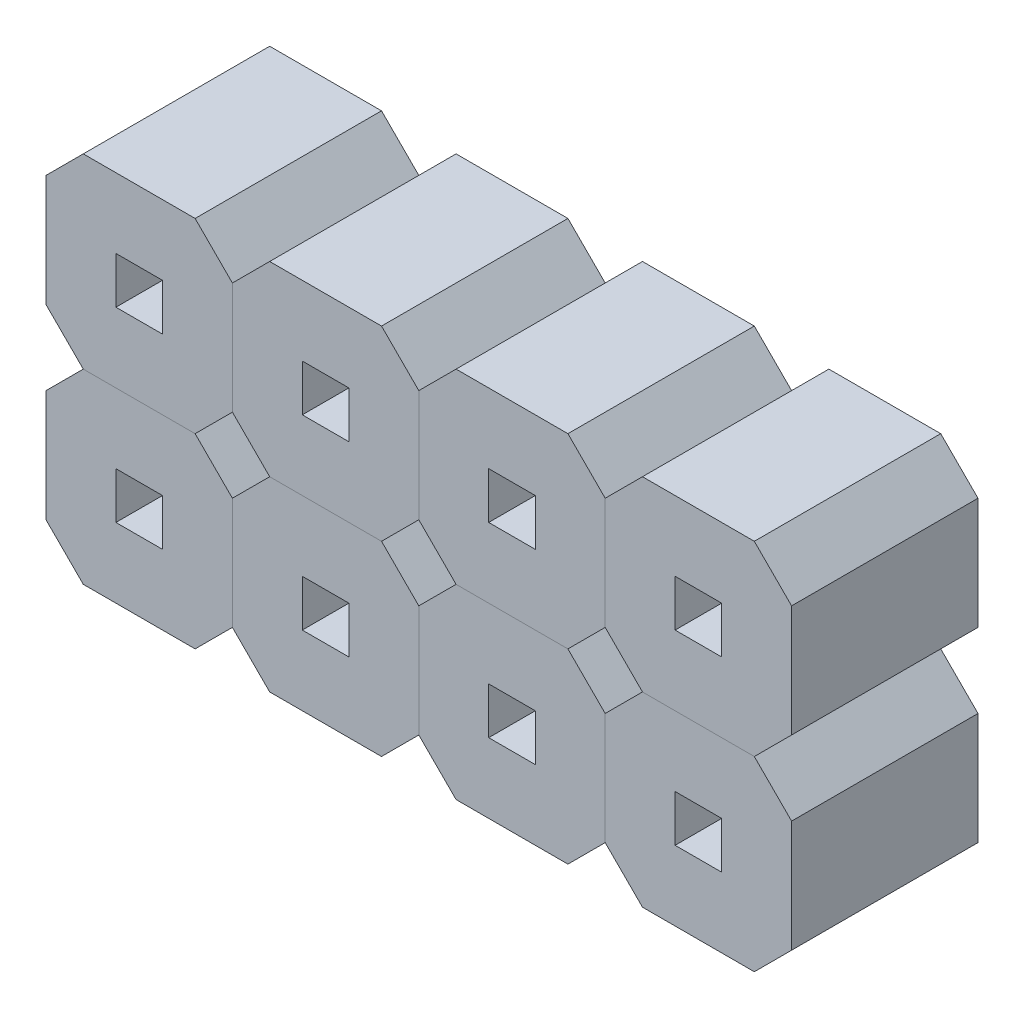
SolidWorks part; units mm, degrees
material "Nylon 6/10"
ref_plane "Front Plane" through (0, 0, 0) normal (0, 0, 1) x (1, 0, 0)
ref_plane "Top Plane" through (0, 0, 0) normal (0, 1, 0) x (1, 0, 0)
ref_plane "Right Plane" through (0, 0, 0) normal (1, 0, 0) x (0, 0, -1)
sketch "Sketch1" plane through (0, 0, 0) normal (0, 0, 1) x (1, 0, 0)
  line L0 (2.032, 2.54) -> (2.54, 2.032)
  line L1 (0.508, 0) -> (2.032, 0)
  line L2 (0, 0.508) -> (0, 2.032)
  line L3 (0.508, 2.54) -> (2.032, 2.54)
  line L4 (2.54, 0.508) -> (2.54, 2.032)
  line L5 (0, 2.032) -> (0.508, 2.54)
  line L6 (0, 0.508) -> (0.508, 0)
  line L7 (2.032, 0) -> (2.54, 0.508)
  line L8 (0.508, 2.54) -> (2.032, 0) construction
  line L10 (0.9525, 0.9525) -> (1.5875, 0.9525)
  line L11 (0.9525, 0.9525) -> (0.9525, 1.5875)
  line L12 (0.9525, 1.5875) -> (1.5875, 1.5875)
  line L13 (1.5875, 0.9525) -> (1.5875, 1.5875)
  line L14 (0.9525, 0.9525) -> (1.5875, 1.5875) construction
  line L15 (0.9525, 1.5875) -> (1.5875, 0.9525) construction
  point P0 (0, 0)
  point P1 (2.54, 2.54)
  point P2 (0, 2.54)
  point P3 (2.54, 0)
  point P13 (1.27, 1.27)
  point P14 (1.27, 1.27)
  dimension "D1" = 2.54
  dimension "D2" = 2.54
  dimension "D3" = 0.635
extrude "Boss-Extrude1" add sketch "Sketch1" along normal blind 2.54
pattern_linear "LPattern1" count 4 spacing 2.54 along (-1, 0, 0) count 2 spacing 2.54 along (0, -1, 0) of bodies 101
